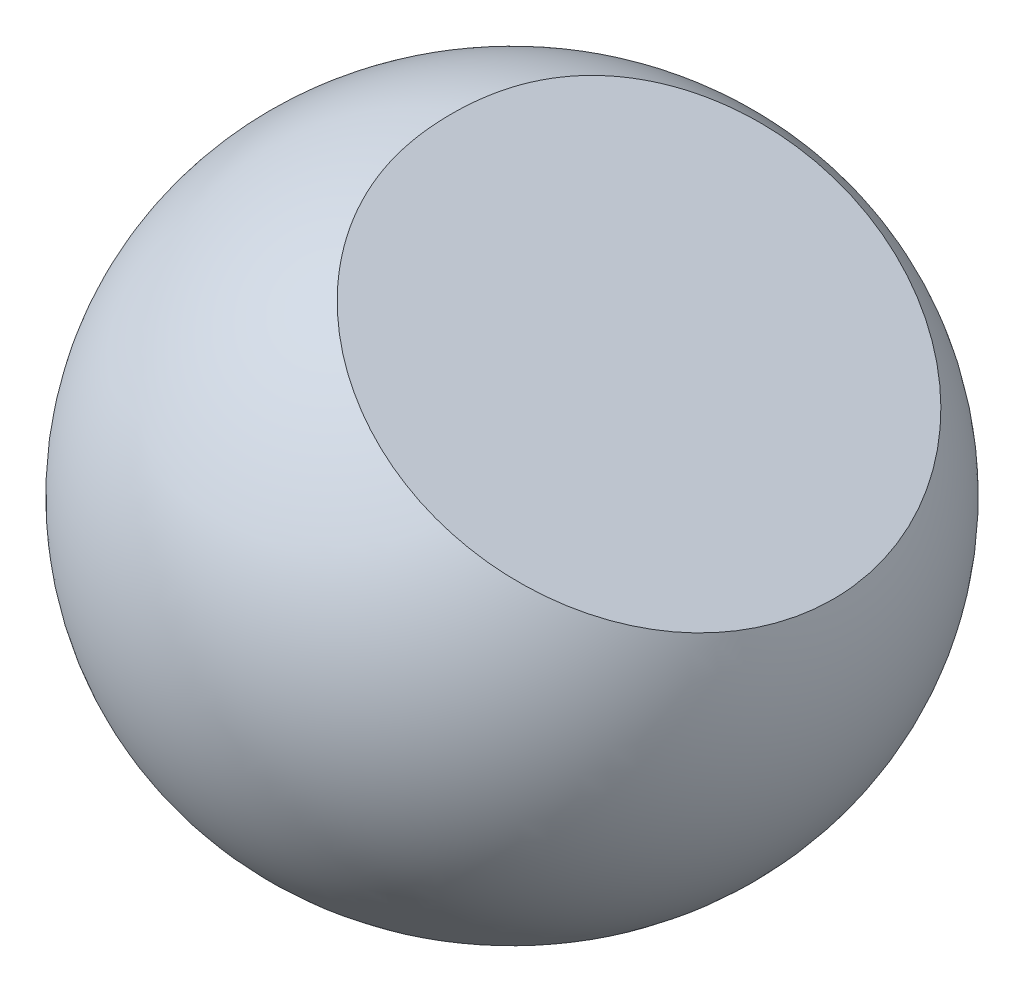
SolidWorks part; units mm, degrees
ref_plane "Front Plane" through (0, 0, 0) normal (0, 0, 1) x (1, 0, 0)
ref_plane "Top Plane" through (0, 0, 0) normal (0, 1, 0) x (1, 0, 0)
ref_plane "Right Plane" through (0, 0, 0) normal (1, 0, 0) x (0, 0, -1)
sketch "Sketch1" plane through (0, 0, 0) normal (0, 0, 1) x (1, 0, 0)
  line L0 (0, 0) -> (0, 49.509) construction
  line L1 (0, 49.509) -> (0, -35)
  line L2 (0, -35) -> (-25.272, -35)
  arc A0 (0, 49.509) -> (-25.272, -35) centre (-4.0728, 4.6937) ccw
  dimension "D2" = 45
  dimension "D1" = 35
revolve "Revolve1" add sketch "Sketch1" angle 360 about L0
sketch "Sketch2" plane through (0, 0, 0) normal (0, 0, 1) x (1, 0, 0)
  line L0 (0, 0) -> (0, 66.1042) construction
  line L1 (-10, 50) -> (48.3009, 15)
  line L2 (48.3009, 15) -> (48.3009, 50)
  line L3 (48.3009, 50) -> (-10, 50)
  dimension "D1" = 68
  dimension "D2" = 50
  dimension "D3" = 10
  dimension "D4" = 35
extrude "Cut-Extrude1" cut sketch "Sketch2" against normal through all both and the other way through all contours L3 L1 L2
